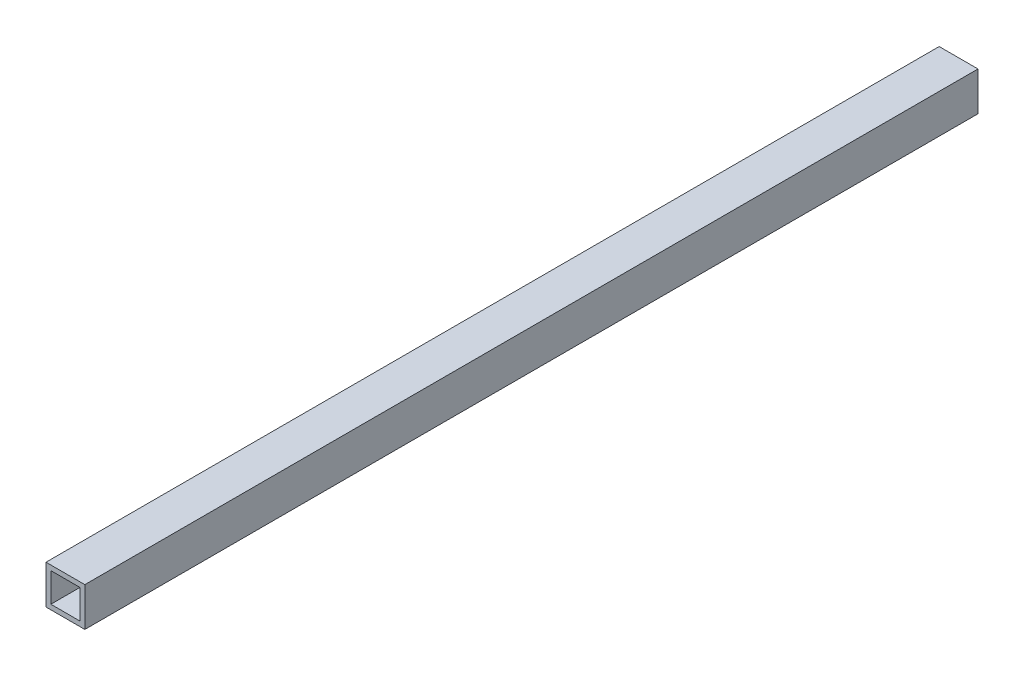
SolidWorks part; units mm, degrees
ref_plane "Front Plane" through (0, 0, 0) normal (0, 0, 1) x (1, 0, 0)
ref_plane "Top Plane" through (0, 0, 0) normal (0, 1, 0) x (1, 0, 0)
ref_plane "Right Plane" through (0, 0, 0) normal (1, 0, 0) x (0, 0, -1)
sketch "Sketch1" plane through (0, 0, 0) normal (0, 0, 1) x (1, 0, 0)
  line L0 (-6.4742, 11.5232) -> (12.5758, 11.5232)
  line L1 (-9.6492, 14.6982) -> (15.7508, 14.6982)
  line L2 (-9.6492, 14.6982) -> (-9.6492, -10.7018)
  line L3 (-9.6492, -10.7018) -> (15.7508, -10.7018)
  line L4 (15.7508, 14.6982) -> (15.7508, -10.7018)
  line L5 (12.5758, 11.5232) -> (12.5758, -7.5268)
  line L6 (-6.4742, -7.5268) -> (12.5758, -7.5268)
  line L7 (-6.4742, 11.5232) -> (-6.4742, -7.5268)
  dimension "D1" = 25.4
  dimension "D2" = 25.4
  dimension "D3" = 3.175
extrude "Boss-Extrude1" add sketch "Sketch1" along normal blind 584.2
